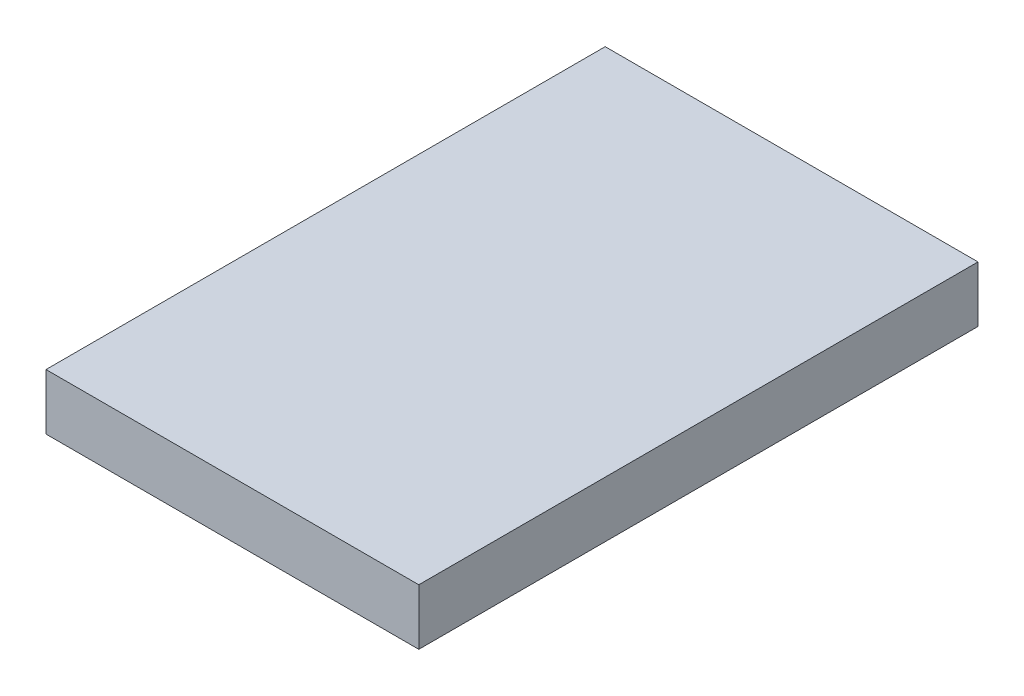
SolidWorks part; units mm, degrees
ref_plane "Front Plane" through (0, 0, 0) normal (0, 0, 1) x (1, 0, 0)
ref_plane "Top Plane" through (0, 0, 0) normal (0, 1, 0) x (1, 0, 0)
ref_plane "Right Plane" through (0, 0, 0) normal (1, 0, 0) x (0, 0, -1)
sketch "Sketch1" plane through (0, 0, 0) normal (0, 1, 0) x (1, 0, 0)
  line L1 (-10.449, 15.0748) -> (9.551, 15.0748)
  line L2 (-10.449, 15.0748) -> (-10.449, -14.9252)
  line L3 (-10.449, -14.9252) -> (9.551, -14.9252)
  line L4 (9.551, 15.0748) -> (9.551, -14.9252)
  dimension "D1" = 20
  dimension "D2" = 30
extrude "Boss-Extrude1" add sketch "Sketch1" along normal blind 3
